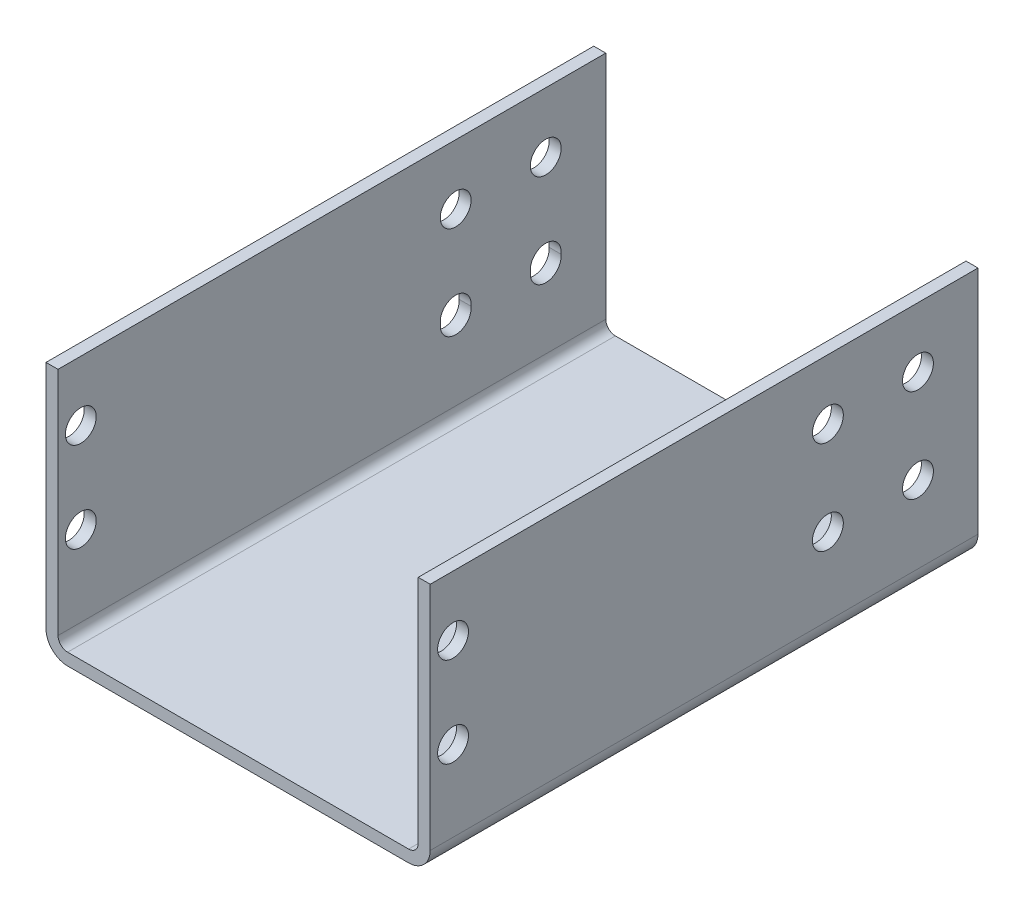
SolidWorks part; units mm, degrees
material "1060 Alloy"
ref_plane "Front Plane" through (0, 0, 0) normal (0, 0, 1) x (1, 0, 0)
ref_plane "Top Plane" through (0, 0, 0) normal (0, 1, 0) x (1, 0, 0)
ref_plane "Right Plane" through (0, 0, 0) normal (1, 0, 0) x (0, 0, -1)
sketch "Sketch1" plane through (0, 0, 0) normal (0, 0, 1) x (1, 0, 0)
  line L0 (1.016, 0) -> (37.084, 0)
  line L1 (0, 1.016) -> (0, 25.4)
  line L2 (38.1, 1.016) -> (38.1, 25.4)
  arc A0 (38.1, 1.016) -> (37.084, 0) centre (37.084, 1.016) cw
  arc A1 (0, 1.016) -> (1.016, 0) centre (1.016, 1.016) ccw
  point P8 (38.1, 0)
  point P11 (0, 0)
  dimension "D3" = 1.016
  dimension "D1" = 38.1
  dimension "D2" = 25.4
extrude "Extrude-Thin1" add sketch "Sketch1" along normal up to surface (57.9355 mm away) thin
hole_wizard "#4 Clearance Hole1" positions "Sketch2" profile "Sketch3" hole size "#4" standard "ANSI Inch"
sketch "Sketch2" plane through (-1.27, -12.402, 98.8948) normal (-1, 0, 0) x (0, 0, 1)
  point P0 (-92.5448, 31.452)
  point P1 (-83.0198, 31.452)
  point P2 (-83.0198, 21.927)
  point P3 (-92.5448, 21.927)
sketch "Sketch3" plane through (-1.27, 19.05, 6.35) normal (0, 1, 0) x (0, 0, 1)
  line L0 (0, 0) -> (0, 1.269)
  line L1 (0, 1.269) -> (1.6319, 1.269)
  line L2 (1.6319, 1.269) -> (1.6319, 0)
  line L5 (1.6319, 0) -> (0, 0)
  line L11 (0, -6.35) -> (0, 107.95) construction
  dimension "Thru Hole Dia." = 3.2639
  dimension "Thru Hole Depth" = 1.269
hole_wizard "#4 Clearance Hole2" positions "Sketch4" profile "Sketch5" hole size "#4" standard "ANSI Inch" end condition through all
sketch "Sketch4" plane through (39.37, -12.402, 98.8948) normal (1, 0, 0) x (0, 0, -1)
  point P0 (92.5448, 31.452)
  point P1 (83.0198, 31.452)
  point P2 (83.0198, 21.5728)
  point P3 (92.5448, 21.5728)
sketch "Sketch5" plane through (39.37, 19.05, 6.35) normal (0, 1, 0) x (0, 0, -1)
  line L0 (0, 0) -> (0, 40.64)
  line L1 (0, 40.64) -> (1.6319, 40.64)
  line L2 (1.6319, 40.64) -> (1.6319, 0)
  line L5 (1.6319, 0) -> (0, 0)
  line L11 (0, -6.35) -> (0, 107.95) construction
  dimension "Thru Hole Dia." = 3.2639
  dimension "Thru Hole Depth" = 40.64
hole_wizard "#4 Clearance Hole3" positions "Sketch6" profile "Sketch7" hole size "#4" standard "ANSI Inch"
sketch "Sketch6" plane through (-1.27, -12.402, 98.8948) normal (-1, 0, 0) x (0, 0, 1)
  point P0 (-43.3723, 31.452)
  point P1 (-43.3723, 21.927)
sketch "Sketch7" plane through (-1.27, 19.05, 55.5225) normal (0, 1, 0) x (0, 0, 1)
  line L0 (0, 0) -> (0, 1.269)
  line L1 (0, 1.269) -> (1.6319, 1.269)
  line L2 (1.6319, 1.269) -> (1.6319, 0)
  line L5 (1.6319, 0) -> (0, 0)
  line L11 (0, -6.35) -> (0, 107.95) construction
  dimension "Thru Hole Dia." = 3.2639
  dimension "Thru Hole Depth" = 1.269
hole_wizard "#4 Clearance Hole4" positions "Sketch8" profile "Sketch9" hole size "#4" standard "ANSI Inch" end condition through all
sketch "Sketch8" plane through (39.37, -12.402, 98.8948) normal (1, 0, 0) x (0, 0, -1)
  point P0 (43.3723, 21.927)
  point P1 (43.3723, 31.452)
sketch "Sketch9" plane through (39.37, 9.525, 55.5225) normal (0, 1, 0) x (0, 0, -1)
  line L0 (0, 0) -> (0, 40.64)
  line L1 (0, 40.64) -> (1.6319, 40.64)
  line L2 (1.6319, 40.64) -> (1.6319, 0)
  line L5 (1.6319, 0) -> (0, 0)
  line L11 (0, -6.35) -> (0, 107.95) construction
  dimension "Thru Hole Dia." = 3.2639
  dimension "Thru Hole Depth" = 40.64
